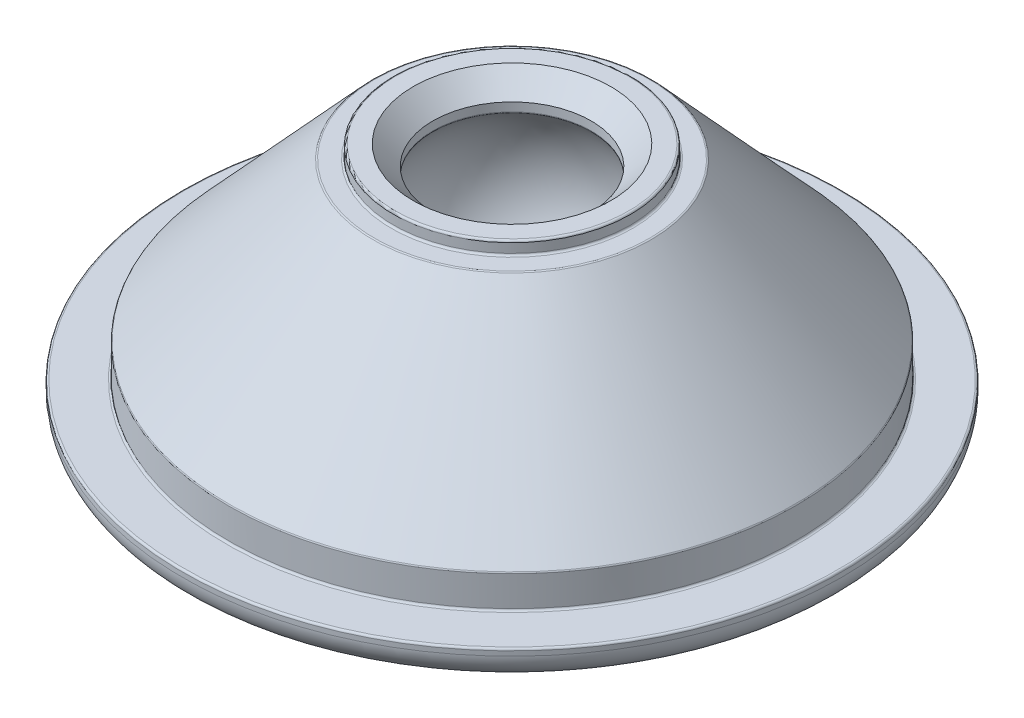
SolidWorks part; units mm, degrees
ref_plane "Front Plane" through (0, 0, 0) normal (0, 0, 1) x (1, 0, 0)
ref_plane "Top Plane" through (0, 0, 0) normal (0, 1, 0) x (1, 0, 0)
ref_plane "Right Plane" through (0, 0, 0) normal (1, 0, 0) x (0, 0, -1)
sketch "Sketch1" plane through (0, 0, 0) normal (0, 0, 1) x (1, 0, 0)
  line L0 (-25, 0) -> (-21.5, 0)
  line L1 (-21.5, 0) -> (-21.5, 2.5)
  line L2 (-21.5, 2.5) -> (-10.5, 14.5)
  line L3 (-10.5, 14.5) -> (-9, 14.5)
  line L4 (-9, 14.5) -> (-9, 15.5)
  line L5 (-9, 15.5) -> (-6, 15.5)
  line L6 (-6, 15.5) -> (-6, 13.2915)
  line L7 (-6, 15.5) -> (0, 15.5) construction
  line L8 (0, 15.5) -> (0, -2.5) construction
  line L9 (0, -2.5) -> (-19, -2.5) construction
  line L10 (-25, 0) -> (-25, -2.5)
  line L11 (-25, -2.5) -> (-19, -2.5)
  line L12 (-19, -2.5) -> (-19, 1.5275)
  line L13 (-9.9247, 11.4279) -> (-19, 1.5275)
  line L14 (0, -2.5) -> (0, 0)
  arc A0 (-6, 13.2915) -> (0, 0) centre (0, 8) ccw
  arc A1 (-9.9247, 11.4279) -> (0, -2.5) centre (0, 8) ccw
  point P33 (-21.5, 1.25)
  dimension "D2" = 8
  dimension "D4" = 2.5
  dimension "D1" = 50
  dimension "D3" = 12
  dimension "D5" = 2.5
  dimension "D6" = 38
  dimension "D7" = 2.5
  dimension "D8" = 2.5
  dimension "D9" = 3
  dimension "D10" = 17
  dimension "D11" = 2.5
  dimension "D12" = 18
  dimension "D13" = 21
revolve "Revolve1" add sketch "Sketch1" angle 360 about L8
fillet "Fillet1" radius 2 2 edges at (-25, -2.5, 0) (-19, -2.5, 0)
fillet "Fillet2" radius 0.15 8 edges at (-19, 1.5275, 0) (-6, 13.2915, 0) (-25, 0, 0) (-21.5, 0, 0) (-21.5, 2.5, 0) (-10.5, 14.5, 0) (-9, 14.5, 0) (-9, 15.5, 0)
chamfer "Chamfer1" distance 1.5 angle 45 1 edges at (-6, 15.5, 0)
